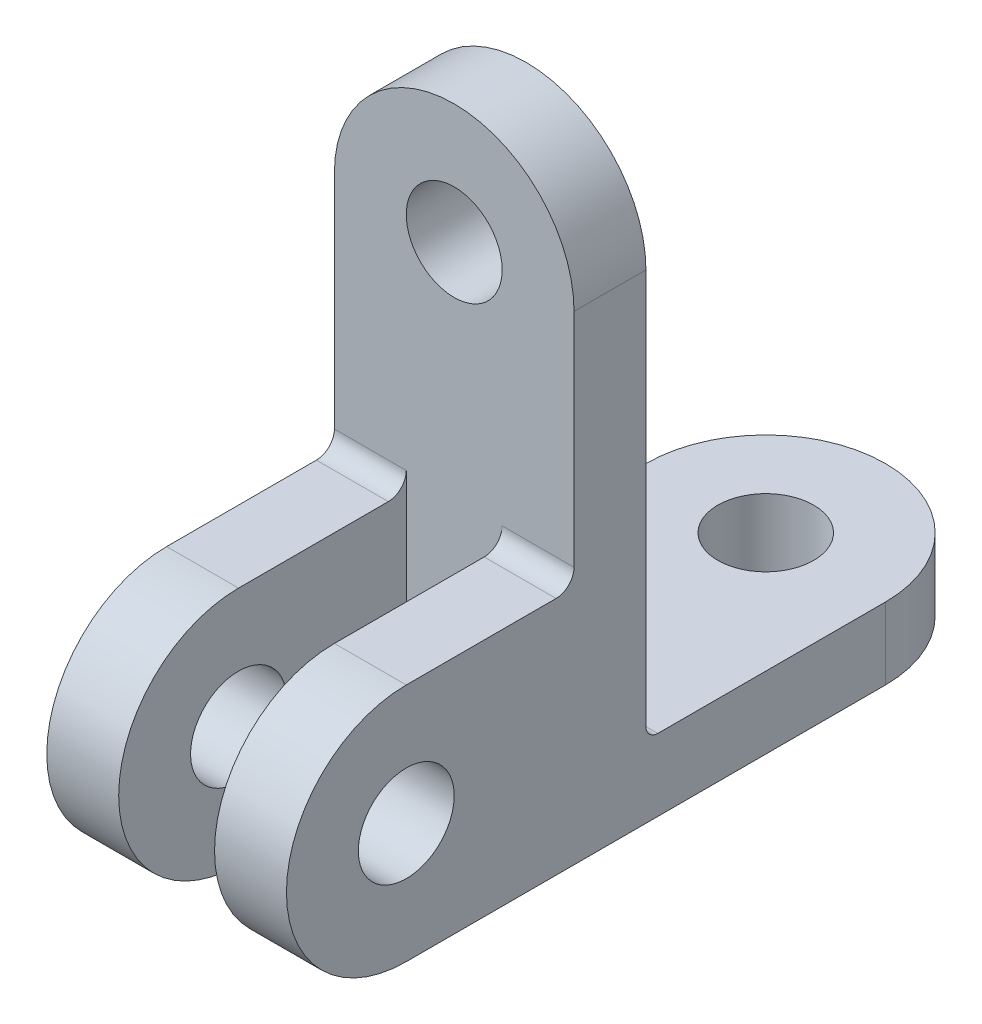
SolidWorks part; units mm, degrees
ref_plane "Front Plane" through (0, 0, 0) normal (1, 0, 0) x (0, 1, 0)
ref_plane "Top Plane" through (0, 0, 0) normal (0, 0, 1) x (0, 1, 0)
ref_plane "Right Plane" through (0, 0, 0) normal (0, 1, 0) x (-1, 0, 0)
sketch "Sketch7" plane through (0, 0, 0) normal (0, 0, 1) x (0, 1, 0)
  line L0 (0, -20) -> (0, 20)
  line L1 (40, 20) -> (0, 20)
  line L2 (40, -20) -> (0, -20)
  arc A0 (40, -20) -> (40, 20) centre (40, 0) ccw
  point P4 (0, 0)
  dimension "D2" = 40
  dimension "D1" = 40
extrude "Boss-Extrude3" add sketch "Sketch7" along normal blind 12
sketch "Sketch8" plane through (0, 0, 0) normal (0, -1, 0) x (1, 0, 0)
  line L0 (0, 0) -> (0, 20.4166) construction
sketch "Sketch9" plane through (0, 0, 0) normal (1, 0, 0) x (0, 1, 0)
  line L0 (0, 0) -> (-40, 0)
  line L1 (-40, 0) -> (-40, 40)
  line L3 (0, 40) -> (0, 0)
  arc A0 (0, 40) -> (-40, 40) centre (-20, 40) ccw
  dimension "D1" = 40
  dimension "D2" = 40
extrude "Boss-Extrude4" add sketch "Sketch9" along normal mid plane 40
sketch "Sketch10" plane through (0, -40, 0) normal (0, -1, 0) x (1, 0, 0)
  line L0 (-20, 0) -> (20, 0)
  line L1 (20, 0) -> (20, -40)
  line L3 (-20, -40) -> (-20, 0)
  arc A0 (-20, -40) -> (20, -40) centre (0, -40) ccw
  dimension "D1" = 20
  dimension "D2" = 40
extrude "Boss-Extrude5" add sketch "Sketch10" against normal blind 12
sketch "Sketch12" plane through (0, 0, 12) normal (0, 0, 1) x (1, 0, 0)
  line L0 (-20, 0) -> (20, 0) construction
  line L1 (-8, 0) -> (8, 0)
  line L2 (-8, 0) -> (-8, -40)
  line L3 (-8, -40) -> (8, -40)
  line L4 (8, 0) -> (8, -40)
  line L5 (20, -40) -> (-20, -40) construction
  point P8 (0, -40)
  dimension "D1" = 16
extrude "Cut-Extrude1" cut sketch "Sketch12" along normal through all
sketch "Sketch13" plane through (20, 0, 0) normal (1, 0, 0) x (0, 1, 0)
  circle A0 centre (-20, 40) radius 8
  dimension "D1" = 16
extrude "Cut-Extrude2" cut sketch "Sketch13" against normal through all
sketch "Sketch14" plane through (0, 0, 12) normal (0, 0, 1) x (1, 0, 0)
  circle A0 centre (0, 40) radius 8
  dimension "D1" = 16
extrude "Cut-Extrude3" cut sketch "Sketch14" against normal through all
sketch "Sketch15" plane through (0, -40, 0) normal (0, -1, 0) x (1, 0, 0)
  circle A0 centre (0, -40) radius 8
  dimension "D1" = 16
extrude "Cut-Extrude4" cut sketch "Sketch15" against normal through all
fillet "Fillet1" radius 3 2 edges at (-14, 0, 12) (14, 0, 12)
fillet "Fillet2" radius 2 1 edges at (0, -28, 0)
